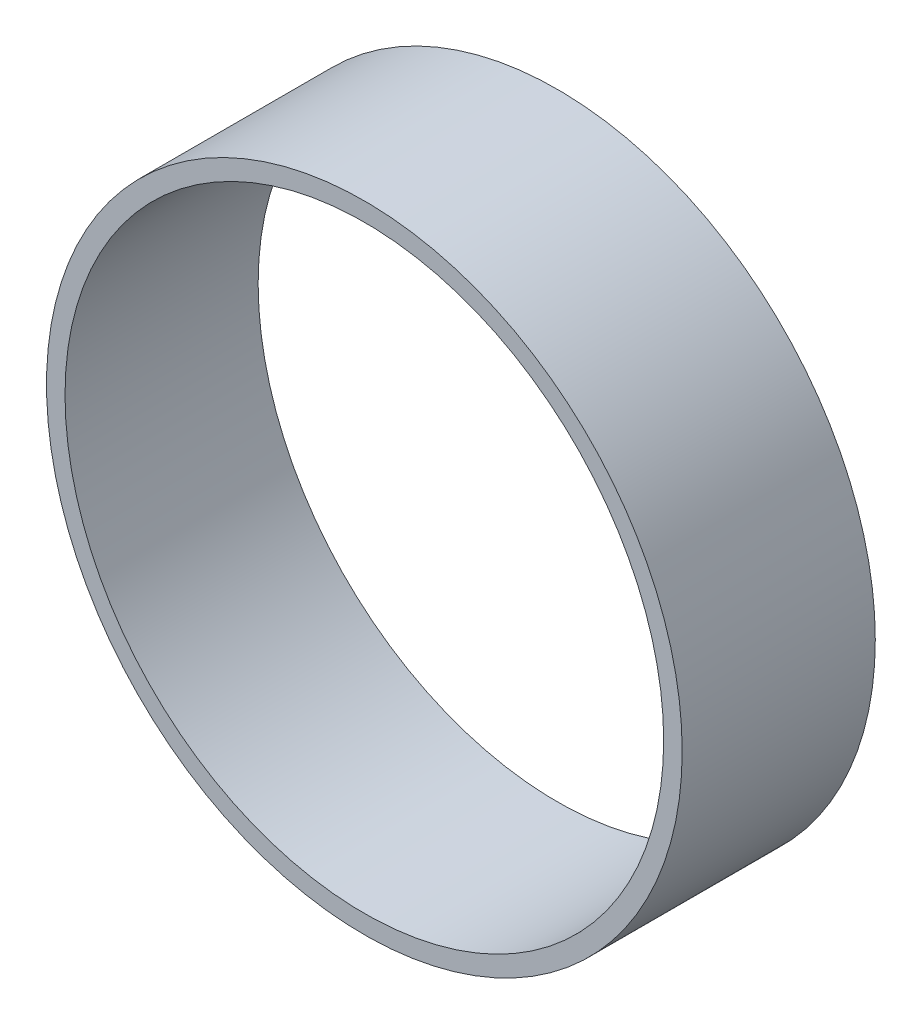
SolidWorks part; units mm, degrees
ref_plane "Plan de face" through (0, 0, 0) normal (0, 0, 1) x (1, 0, 0)
ref_plane "Plan de dessus" through (0, 0, 0) normal (0, 1, 0) x (1, 0, 0)
ref_plane "Plan de droite" through (0, 0, 0) normal (1, 0, 0) x (0, 0, -1)
sketch "Esquisse1" plane through (0, 0, 0) normal (0, 0, 1) x (1, 0, 0)
  circle A0 centre (0, 0) radius 19.75
  circle A1 centre (0, 0) radius 18.6
  dimension "D1" = 39.5
  dimension "D2" = 37.2
extrude "Boss.-Extru.1" add sketch "Esquisse1" along normal blind 12
